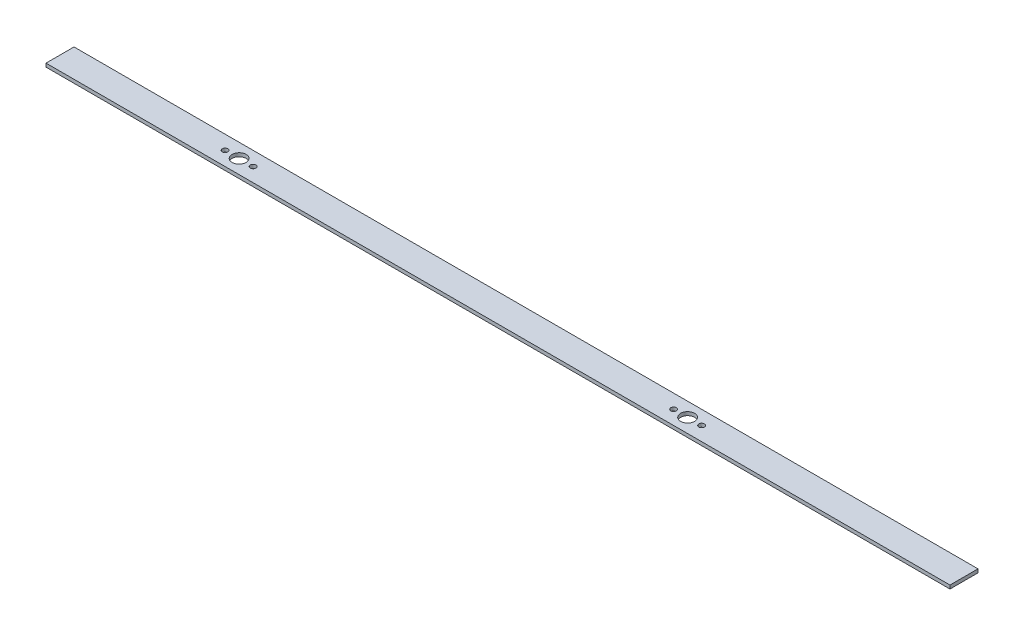
SolidWorks part; units mm, degrees
material "6061-T6 (SS)"
ref_plane "Front Plane" through (0, 0, 0) normal (0, 0, 1) x (1, 0, 0)
ref_plane "Top Plane" through (0, 0, 0) normal (0, 1, 0) x (1, 0, 0)
ref_plane "Right Plane" through (0, 0, 0) normal (1, 0, 0) x (0, 0, -1)
sketch "Sketch1" plane through (0, 0, 0) normal (0, 1, 0) x (1, 0, 0)
  line L1 (0, 0) -> (819.15, 0)
  line L2 (0, 0) -> (0, 25.4)
  line L3 (0, 25.4) -> (819.15, 25.4)
  line L4 (819.15, 0) -> (819.15, 25.4)
  dimension "D1" = 25.4
  dimension "D2" = 819.15
extrude "Boss-Extrude1" add sketch "Sketch1" along normal blind 3.175
sketch "Sketch2" plane through (0, 3.175, 0) normal (0, 1, 0) x (1, 0, 0)
  circle A0 centre (149.5978, 12.7) radius 2.5146 construction
  circle A1 centre (174.9978, 12.7) radius 2.5146 construction
  circle A2 centre (555.9978, 12.7) radius 2.5146 construction
  circle A3 centre (581.3978, 12.7) radius 2.5146 construction
  circle A4 centre (149.5978, 12.7) radius 2.5146
  circle A5 centre (174.9978, 12.7) radius 2.5146
  circle A6 centre (555.9978, 12.7) radius 2.5146
  circle A7 centre (581.3978, 12.7) radius 2.5146
  circle A8 centre (162.2978, 12.7) radius 6.35
  circle A9 centre (568.6978, 12.7) radius 6.35
  dimension "D1" = 12.7
  dimension "D2" = 12.7
  dimension "D3" = 12.7
extrude "Cut-Extrude1" cut sketch "Sketch2" against normal through all
